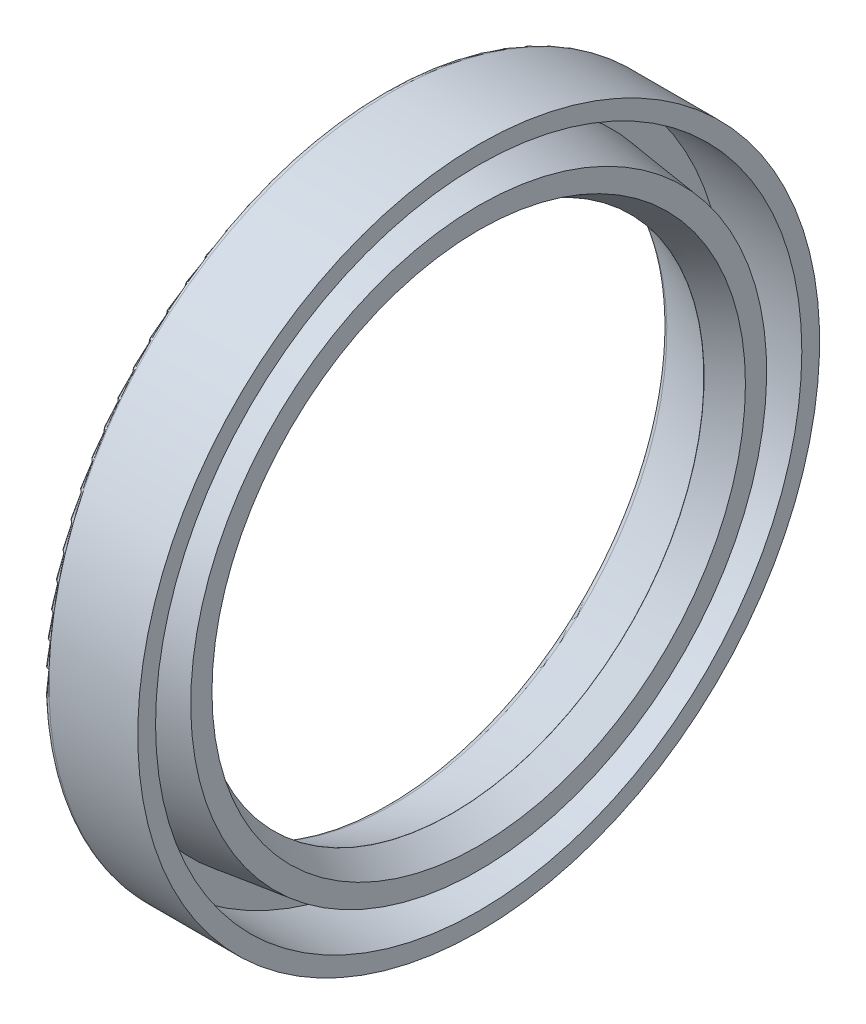
SolidWorks part; units mm, degrees
material "O-Ring (NBR)"
ref_plane "Front Plane" through (0, 0, 0) normal (0, 0, 1) x (1, 0, 0)
ref_plane "Top Plane" through (0, 0, 0) normal (0, 1, 0) x (1, 0, 0)
ref_plane "Right Plane" through (0, 0, 0) normal (1, 0, 0) x (0, 0, -1)
sketch "Sketch1" plane through (0, 0, 0) normal (0, 0, 1) x (1, 0, 0)
  line L0 (0.9025, 9.7142) -> (0.9025, 8.9976)
  line L1 (0.005, 8.5) -> (0.9025, 8.9976)
  line L2 (0, 8.5) -> (0.005, 8.5)
  line L3 (-1.969, 9.2189) -> (0, 8.5)
  line L6 (-1.6975, 10.9) -> (-1.6975, 10.0392)
  line L7 (-1.6975, 10.0392) -> (0.9025, 9.7142)
  line L9 (-2.0975, 11.5) -> (0.9025, 11.5)
  line L13 (0.9025, 11.5) -> (0.9025, 10.9)
  line L14 (-1.6975, 10.9) -> (0.9025, 10.9)
  line L23 (0, 0) -> (-1.3995, 0) construction
  line L24 (0, 0) -> (0, 2.1633) construction
  line L25 (-2.2975, 11.3) -> (-2.2975, 9.6886)
  line L26 (0, 0) -> (6.9793, 0) construction
  arc A1 (-2.2975, 9.6886) -> (-1.969, 9.2189) centre (-1.7975, 9.6886) ccw
  arc A2 (-2.0975, 11.5) -> (-2.2975, 11.3) centre (-2.0975, 11.3) ccw
  point P0 (0, 5.2087)
  point P26 (-2.2975, 10.4943)
  dimension "D2" = 23
  dimension "D1" = 17
  dimension "D4" = 3.2
  dimension "D5" = 0.5
  dimension "D3" = 0.6
  dimension "D8" = 0.2
  dimension "D6" = 0.6
  dimension "D7" = 90
revolve "Revolve2" add sketch "Sketch1" angle 360 about L23
